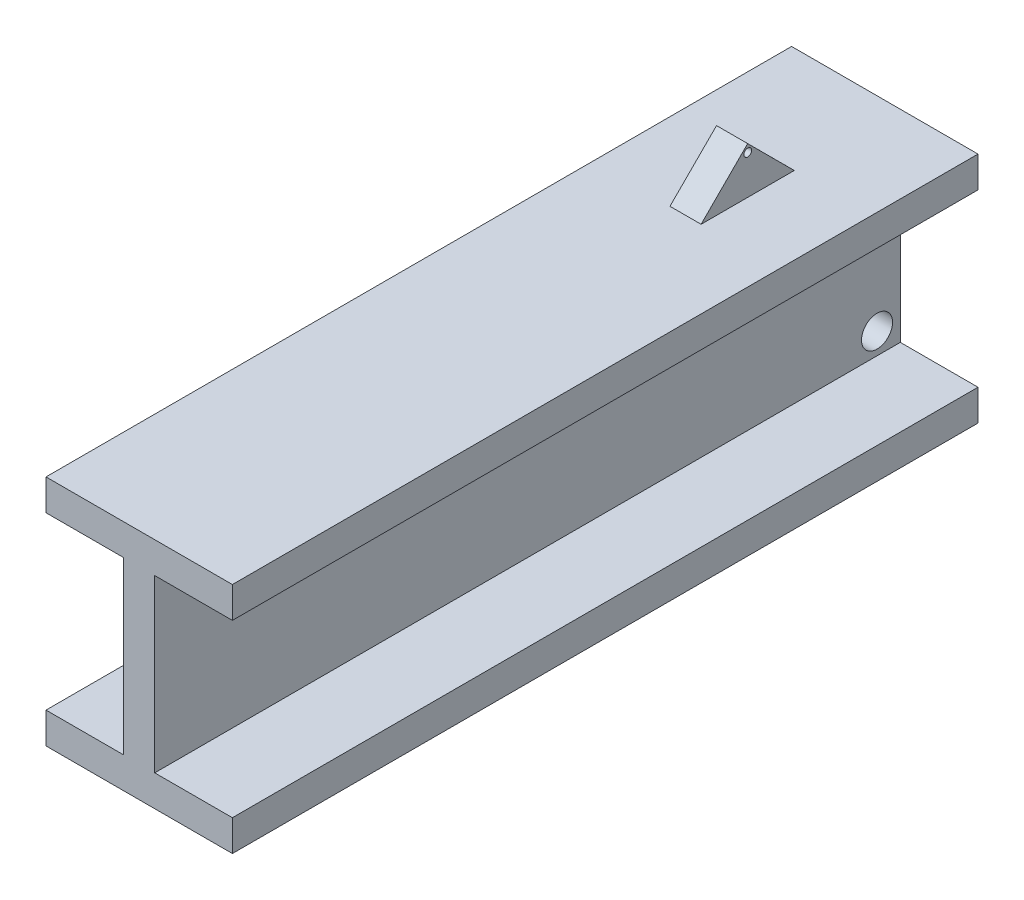
SolidWorks part; units mm, degrees
ref_plane "Front Plane" through (0, 0, 0) normal (0, 0, 1) x (1, 0, 0)
ref_plane "Top Plane" through (0, 0, 0) normal (0, 1, 0) x (1, 0, 0)
ref_plane "Right Plane" through (0, 0, 0) normal (1, 0, 0) x (0, 0, -1)
sketch "Sketch1" plane through (0, 0, 0) normal (0, 0, 1) x (1, 0, 0)
  line L1 (-152.4, 190.5) -> (152.4, 190.5)
  line L2 (-152.4, 190.5) -> (-152.4, -190.5)
  line L3 (-152.4, -190.5) -> (152.4, -190.5)
  line L4 (152.4, 190.5) -> (152.4, -190.5)
  line L5 (-152.4, 190.5) -> (152.4, -190.5) construction
  line L6 (-152.4, -190.5) -> (152.4, 190.5) construction
  line L11 (279.4, -139.7) -> (25.4, -139.7)
  line L12 (279.4, -139.7) -> (279.4, 139.7)
  line L13 (279.4, 139.7) -> (25.4, 139.7)
  line L14 (25.4, -139.7) -> (25.4, 139.7)
  line L15 (279.4, -139.7) -> (25.4, 139.7) construction
  line L16 (279.4, 139.7) -> (25.4, -139.7) construction
  line L17 (-279.4, -139.7) -> (-25.4, -139.7)
  line L18 (-279.4, -139.7) -> (-279.4, 139.7)
  line L19 (-279.4, 139.7) -> (-25.4, 139.7)
  line L20 (-25.4, -139.7) -> (-25.4, 139.7)
  line L21 (-279.4, -139.7) -> (-25.4, 139.7) construction
  line L22 (-279.4, 139.7) -> (-25.4, -139.7) construction
  point P0 (0, 0)
  point P6 (152.4, 0)
  point P11 (-152.4, 0)
  dimension "D1" = 381
  dimension "D2" = 304.8
  dimension "D3" = 279.4
  dimension "D4" = 254
  dimension "D5" = 279.4
  dimension "D6" = 254
extrude "Boss-Extrude1" add sketch "Sketch1" along normal blind 1219.2 contours L20 L17 L2 L3 L4 L11 L14 L13 L1 L19
sketch "Sketch3" plane through (25.4, 0, 0) normal (1, 0, 0) x (0, 0, -1)
  line L0 (-249.6814, 190.5) -> (-249.6814, 266.7)
  line L1 (-1219.2, 190.5) -> (0, 190.5) construction
  line L2 (-249.6814, 266.7) -> (-325.8487, 190.5)
  line L3 (-325.8487, 190.5) -> (-173.4487, 190.5)
  line L4 (-173.4487, 190.5) -> (-249.6814, 266.7)
  dimension "D1" = 76.2
extrude "Boss-Extrude2" add sketch "Sketch3" along normal blind 0.0722 and the other way blind 50.8722 contours L2 L3 L0 | L3 L4 L0
sketch "Sketch4" plane through (25.4, 0, 0) normal (1, 0, 0) x (0, 0, -1)
  line L0 (-249.6814, 266.7) -> (-249.6487, 190.5)
  line L1 (-325.8487, 190.5) -> (-173.4487, 190.5) construction
  line L2 (-249.6487, 190.5) -> (-859.2487, 190.5)
  line L3 (-1219.2, 190.5) -> (0, 190.5) construction
  line L4 (-859.2487, -190.5) -> (-859.2487, -266.7)
  line L5 (-1219.2, -190.5) -> (0, -190.5) construction
  line L6 (-859.2487, -266.7) -> (-781.9133, -190.5)
  line L7 (-781.9133, -190.5) -> (-934.33, -190.5)
  line L8 (-934.33, -190.5) -> (-859.2487, -266.7)
  dimension "D1" = 609.6
  dimension "D2" = 76.2
extrude "Boss-Extrude3" add sketch "Sketch4" along normal blind 0.0722 and the other way blind 50.8722 contours L7 L8 L4 | L6 L7 L4
sketch "Sketch6" plane through (25.4, 0, 0) normal (1, 0, 0) x (0, 0, -1)
  line L0 (0, 0) -> (0, 139.7)
  line L1 (0, 139.7) -> (0, 69.85)
  line L2 (0, 69.85) -> (0, 139.7)
  line L3 (0, 104.775) -> (-38.1, 104.775)
  line L4 (-38.1, 104.775) -> (-38.1, -139.7)
  line L5 (-1219.2, -139.7) -> (0, -139.7) construction
  line L6 (-38.1, -139.7) -> (0, -139.7)
  line L7 (0, -139.7) -> (0, 0)
  line L8 (0, -69.85) -> (0, -139.7)
  line L9 (0, -139.7) -> (0, 0)
  line L10 (0, -69.85) -> (0, -139.7)
  line L11 (0, -104.775) -> (-38.1, -104.775)
  circle A0 centre (-38.1, 104.775) radius 25.4
  circle A1 centre (-38.1, -104.775) radius 25.4
  dimension "D1" = 38.1
extrude "Cut-Extrude1" cut sketch "Sketch6" against normal blind 101.6 and the other way blind 101.6 contours L3 A0 L4 | L4 A0 L3 | L4 A1 | L11 A1 L4 | L4 A1 L11
sketch "Sketch7" plane through (25.4722, 0, 0) normal (1, 0, 0) x (0, 0, -1)
  line L0 (-249.6814, 266.7) -> (-249.6814, 254)
  line L1 (-859.2487, -266.7) -> (-859.2487, -254)
  circle A0 centre (-249.6814, 254) radius 6.35
  circle A1 centre (-859.2487, -254) radius 6.35
  dimension "D2" = 12.7
  dimension "D1" = 12.7
extrude "Cut-Extrude3" cut sketch "Sketch7" against normal blind 76.2 and the other way blind 76.2
sketch "Sketch8" plane through (0, 0, 0) normal (0, 0, 1) x (1, 0, 0)
  line L0 (25.4, 0) -> (0, 0)
  line L1 (25.4, -139.7) -> (25.4, 139.7) construction
  line L2 (0, 0) -> (-25.4, 0)
  line L3 (-25.4, -139.7) -> (-25.4, 139.7) construction
  line L4 (-25.4, 0) -> (-25.4, 14.1978)
  line L5 (-25.4, 14.1978) -> (25.4, 14.1978)
  line L6 (25.4, 14.1978) -> (25.4, 0)
